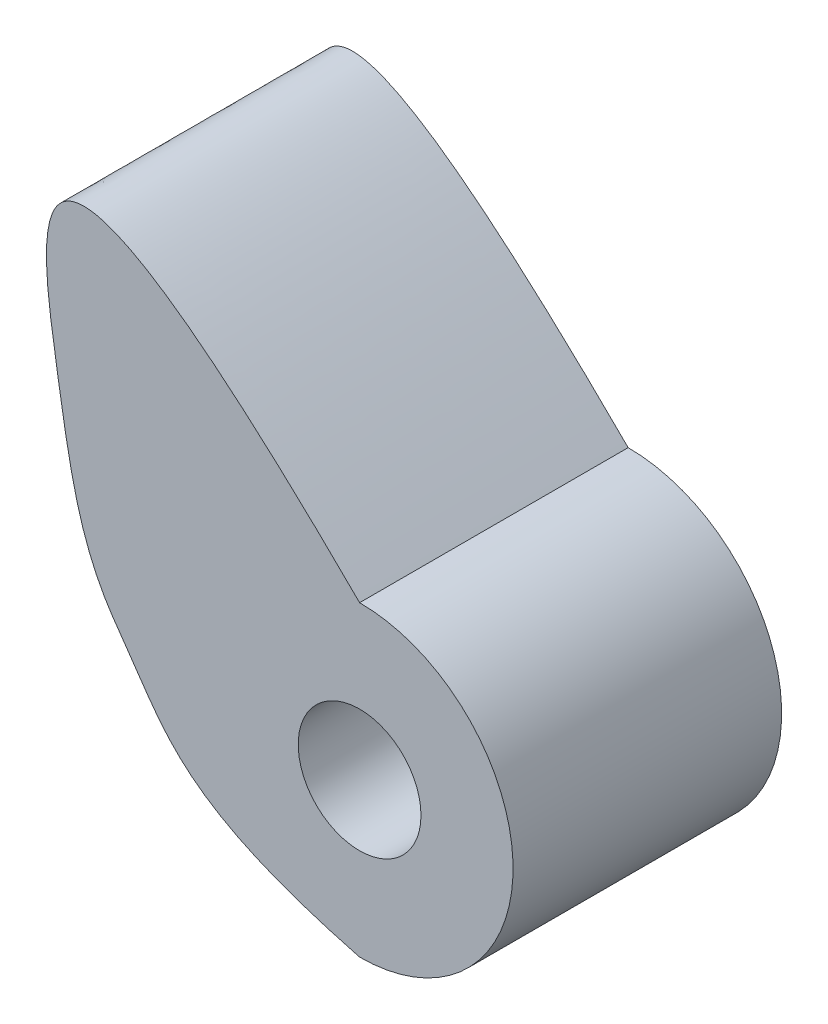
SolidWorks part; units mm, degrees
ref_plane "Plan de face" through (0, 0, 0) normal (0, 0, 1) x (1, 0, 0)
ref_plane "Plan de dessus" through (0, 0, 0) normal (0, 1, 0) x (1, 0, 0)
ref_plane "Plan de droite" through (0, 0, 0) normal (1, 0, 0) x (0, 0, -1)
sketch "Esquisse1" plane through (0, 0, 0) normal (0, 0, 1) x (1, 0, 0)
  line L0 (0, 0) -> (-19.4978, 22.7999) construction
  circle A0 centre (0, 0) radius 4
  circle A1 centre (0, 0) radius 10
  spline S0 degree 3 poles (0, -10) (-11.0713, -7.1147) (-12.8118, -3.2884) (-18.198, 3.9307) (-19.7234, 13.1857) (-22.7754, 32.7011) (0, 10) knots 0 0 0 0 0.306433 0.369658 0.632254 1 1 1 1
  point P6 (-13.9708, -2.3441)
  point P7 (-19.7053, 13.8354)
  point P8 (-21.7295, 20.684)
  point P9 (-15.7458, 0.6597)
  dimension "D1" = 8
  dimension "D2" = 20
  dimension "D3" = 30
extrude "Boss.-Extru.2" add sketch "Esquisse1" against normal blind 17.5
